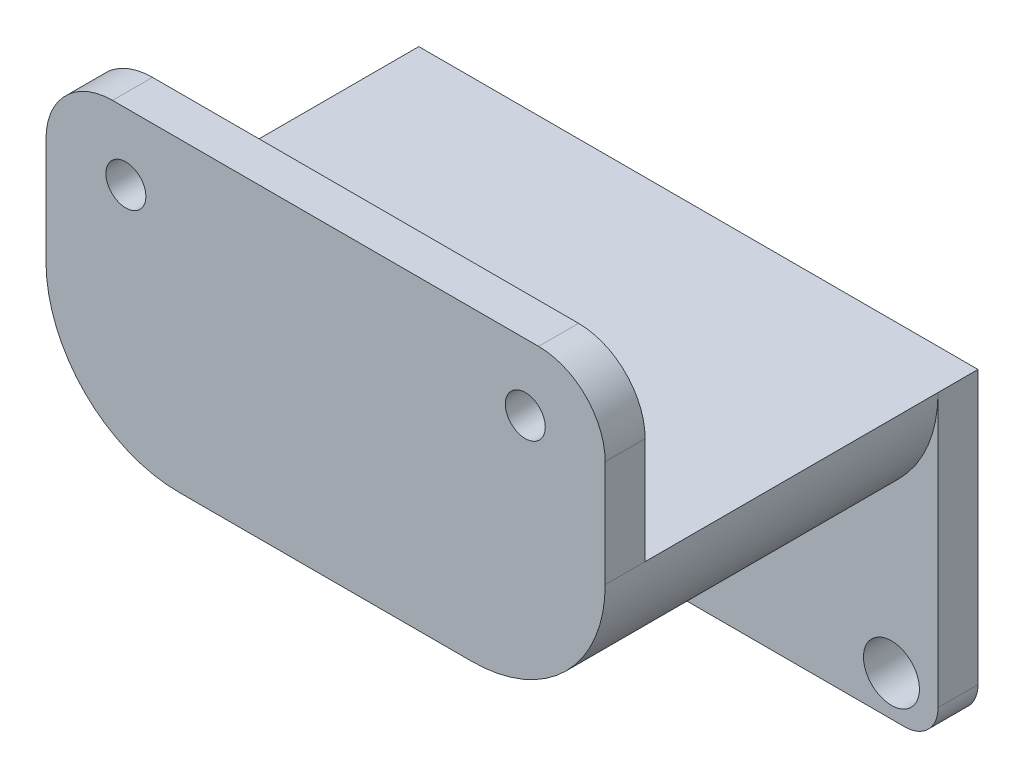
SolidWorks part; units mm, degrees
ref_plane "Front Plane" through (0, 0, 0) normal (0, 0, 1) x (1, 0, 0)
ref_plane "Top Plane" through (0, 0, 0) normal (0, 1, 0) x (1, 0, 0)
ref_plane "Right Plane" through (0, 0, 0) normal (1, 0, 0) x (0, 0, -1)
sketch "Sketch3" plane through (0, 0, 0) normal (0, 0, 1) x (1, 0, 0)
  line L0 (-22.5928, 16.5094) -> (-6.0928, 16.5094)
  line L1 (-48.0928, 16.5094) -> (-31.5928, 16.5094)
  line L2 (-48.0928, 16.5094) -> (-48.0928, 3.5094)
  line L3 (-38.0928, -6.4906) -> (-16.0928, -6.4906)
  line L4 (-6.0928, 16.5094) -> (-6.0928, 3.5094)
  line L5 (-31.5928, 16.5094) -> (-22.5928, 16.5094)
  circle A1 centre (-42.0928, 11.5094) radius 1.5
  circle A2 centre (-12.0928, 11.5094) radius 1.5
  arc A3 (-48.0928, 3.5094) -> (-38.0928, -6.4906) centre (-38.0928, 3.5094) ccw
  arc A4 (-16.0928, -6.4906) -> (-6.0928, 3.5094) centre (-16.0928, 3.5094) ccw
  point P12 (-27.0928, -6.4906)
  point P16 (-48.0928, -6.4906)
  dimension "D4" = 3
  dimension "D5" = 3
  dimension "D12" = 10
  dimension "D13" = 10
  dimension "D1" = 42
  dimension "D2" = 23
  dimension "D6" = 18
  dimension "D7" = 30
  dimension "D8" = 18
  dimension "D9" = 15
  dimension "D10" = 15
extrude "Boss-Extrude3" add sketch "Sketch3" along normal blind 3
sketch "Sketch6" plane through (0, 0, 0) normal (0, 0, 1) x (1, 0, 0)
  line L3 (-38.0928, -6.4906) -> (-16.0928, -6.4906)
  line L6 (-6.0928, 3.5094) -> (-48.0928, 3.5094)
  arc A3 (-48.0928, 3.5094) -> (-38.0928, -6.4906) centre (-38.0928, 3.5094) ccw
  arc A4 (-16.0928, -6.4906) -> (-6.0928, 3.5094) centre (-16.0928, 3.5094) ccw
extrude "Boss-Extrude4" add sketch "Sketch6" against normal blind 25
ref_plane "Plane7" through (0, 3.5094, 0) normal (0, 1, 0) x (1, 0, 0)
sketch "Sketch9" plane through (0, 3.5094, 0) normal (0, 1, 0) x (1, 0, 0)
  line L1 (-6.0928, 25) -> (-48.0928, 25)
  line L2 (-6.0928, 25) -> (-6.0928, 22)
  line L3 (-6.0928, 22) -> (-48.0928, 22)
  line L4 (-48.0928, 25) -> (-48.0928, 22)
  dimension "D1" = 42
  dimension "D2" = 3
fillet "Fillet4" radius 5 2 edges at (-48.0928, 16.5094, 1.5) (-6.0928, 16.5094, 1.5)
extrude "Boss-Extrude7" add sketch "Sketch9" against normal blind 30
fillet "Fillet6" radius 5 1 edges at (-6.0928, -26.4906, -23.5)
fillet "Fillet7" radius 5 1 edges at (-48.0928, -26.4906, -23.5)
ref_plane "Plane13" through (0, 0, -25) normal (0, 0, -1) x (-1, 0, 0)
sketch "Sketch11" plane through (0, 0, -25) normal (0, 0, -1) x (-1, 0, 0)
  line L0 (6.0928, -19.4906) -> (6.0928, 5.5094) construction
  line L3 (22.5928, -24.4906) -> (31.5928, -24.4906)
  line L4 (48.0928, 5.5094) -> (48.0928, -19.4906) construction
  arc A0 (31.5928, -24.4906) -> (22.5928, -24.4906) centre (27.0928, -24.4906) ccw
  circle A1 centre (9.5928, -16.4906) radius 2.1
  circle A2 centre (44.5928, -16.4906) radius 2.1
  dimension "D4" = 8
  dimension "D1" = 4.2
  dimension "D2" = 35
  dimension "D3" = 17.5
  dimension "D5" = 8
  dimension "D6" = 17.5
  dimension "D7" = 21
  dimension "D8" = 21
  dimension "D9" = 3.5
  dimension "D10" = 3.5
extrude "Cut-Extrude2" cut sketch "Sketch11" against normal blind 30
sketch "Sketch12" plane through (0, 0, -25) normal (0, 0, -1) x (-1, 0, 0)
  line L2 (6.0928, -19.4906) -> (50.3785, -19.4906)
  line L3 (6.0928, -19.4906) -> (6.0928, -28.2171)
  line L4 (6.0928, -28.2171) -> (50.3785, -28.2171)
  line L5 (50.3785, -19.4906) -> (50.3785, -28.2171)
extrude "Cut-Extrude3" cut sketch "Sketch12" against normal blind 10
fillet "Fillet8" radius 2.5 2 edges at (-48.0928, -19.4906, -23.5) (-6.0928, -19.4906, -23.5)
